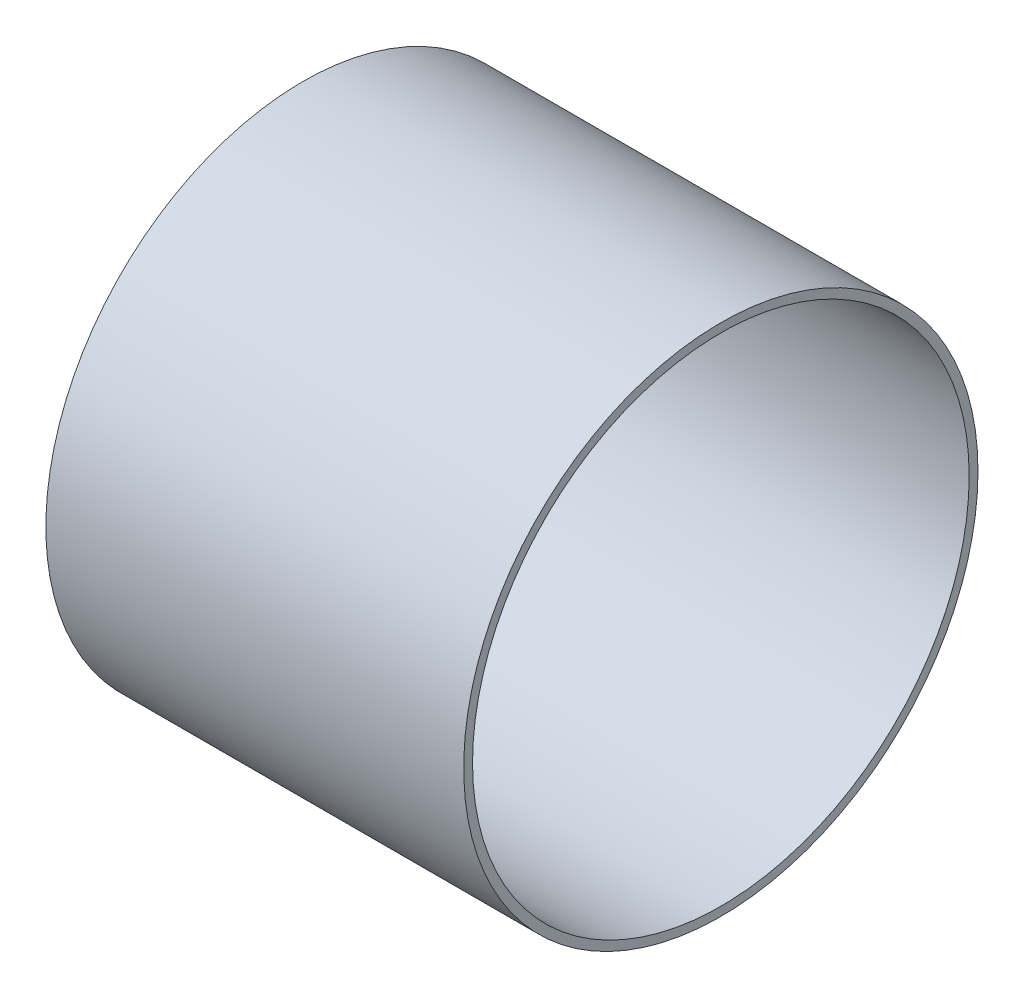
SolidWorks part; units mm, degrees
ref_plane "Front" through (0, 0, 0) normal (0, 0, 1) x (1, 0, 0)
ref_plane "Top" through (0, 0, 0) normal (0, 1, 0) x (1, 0, 0)
ref_plane "Right" through (0, 0, 0) normal (1, 0, 0) x (0, 0, -1)
sketch "Sketch1" plane through (0, 0, 0) normal (1, 0, 0) x (0, 0, -1)
  circle A0 centre (0, 0) radius 109.5375
  circle A1 centre (0, 0) radius 105.7783
  point P4 (109.5375, 0)
  point P5 (105.7783, 0)
  dimension "Pipe OD" = 219.075
  dimension "ID" = 211.5566
  dimension "Wall" = 3.7592
extrude "Extrude1" add sketch "Sketch1" along normal mid plane 178
